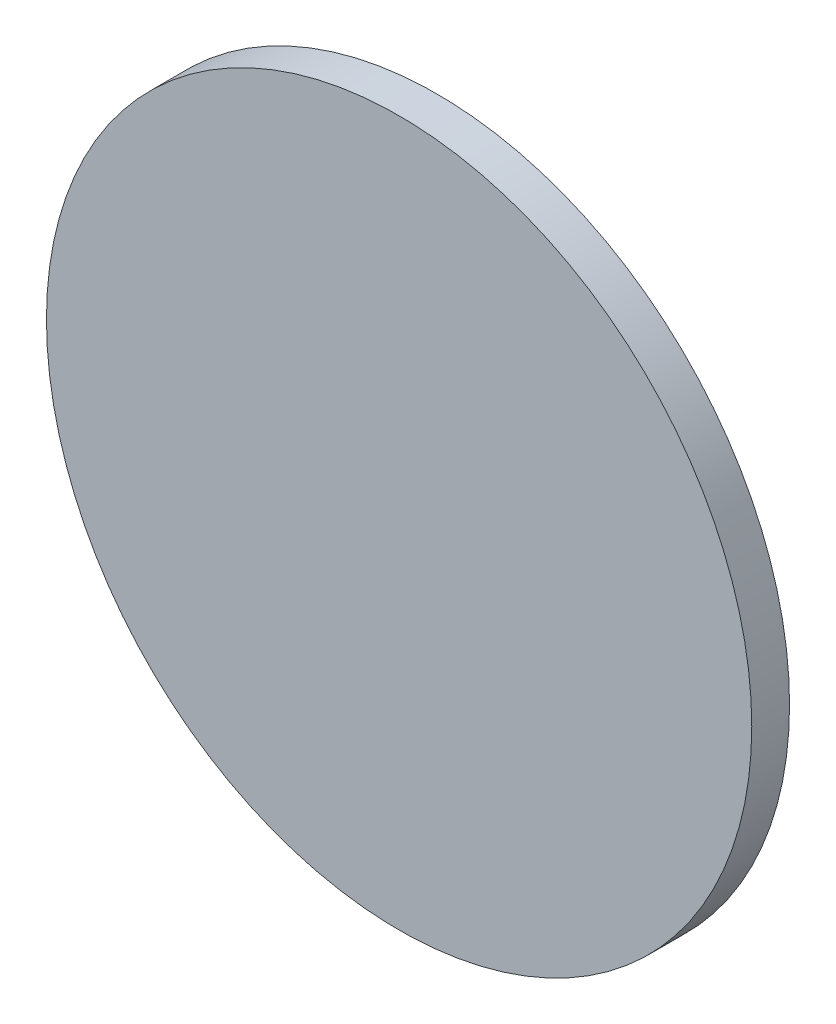
SolidWorks part; units mm, degrees
ref_plane "Front Plane" through (0, 0, 0) normal (0, 0, 1) x (1, 0, 0)
ref_plane "Top Plane" through (0, 0, 0) normal (0, 1, 0) x (1, 0, 0)
ref_plane "Right Plane" through (0, 0, 0) normal (1, 0, 0) x (0, 0, -1)
sketch "Sketch1" plane through (0, 0, 0) normal (0, 0, 1) x (1, 0, 0)
  circle A0 centre (0, 0) radius 177.8
  dimension "D1" = 355.6
extrude "Boss-Extrude1" add sketch "Sketch1" along normal blind 19.05 contours A0
equation "\"prop_diameter\"=14"
equation "\"D1@Sketch1\"=\"prop_diameter\""
equation "\"prop_depth\"=0.75"
equation "\"D1@Boss-Extrude1\"=\"prop_depth\""
